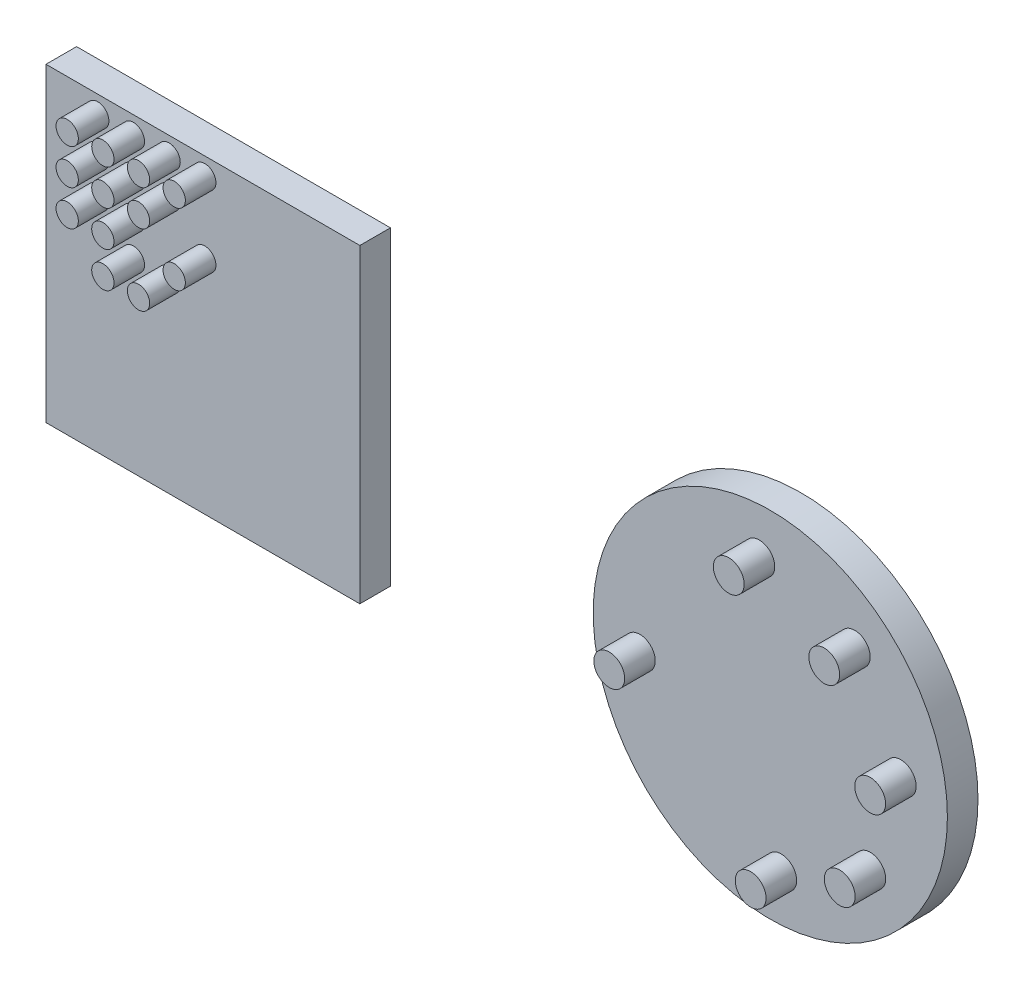
SolidWorks part; units mm, degrees
ref_plane "정면" through (0, 0, 0) normal (0, 0, 1) x (1, 0, 0)
ref_plane "윗면" through (0, 0, 0) normal (0, 1, 0) x (1, 0, 0)
ref_plane "우측면" through (0, 0, 0) normal (1, 0, 0) x (0, 0, -1)
sketch "스케치1" plane through (0, 0, 0) normal (0, 0, 1) x (1, 0, 0)
  circle A0 centre (-7.0097, -12.8826) radius 21.8715
extrude "보스-돌출1" add sketch "스케치1" along normal blind 60
sketch "스케치2" plane through (0, 0, 0) normal (0, 0, -1) x (-1, 0, 0)
  line L1 (-507.2126, 21.9087) -> (108.5736, 21.9087)
  line L2 (-507.2126, 21.9087) -> (-507.2126, -587.0489)
  line L3 (-507.2126, -587.0489) -> (108.5736, -587.0489)
  line L4 (108.5736, 21.9087) -> (108.5736, -587.0489)
  point P4 (-303.0554, 21.9087)
  point P5 (-507.2126, -587.0489)
extrude "보스-돌출2" add sketch "스케치2" along normal blind 60
pattern_linear "선형 패턴1" count 4 spacing 70 along (1, 0, 0) count 4 spacing 70 along (0, -1, 0) skipping (0, 3), (2, 2), (3, 1), (3, 3) of "보스-돌출1"
sketch "스케치3" plane through (0, 0, 0) normal (0, 0, 1) x (1, 0, 0)
  circle A0 centre (1372.5403, -312.891) radius 347.5261
extrude "보스-돌출3" add sketch "스케치3" along normal blind 60 separate body
sketch "스케치4" plane through (0, 0, 60) normal (0, 0, 1) x (1, 0, 0)
  circle A0 centre (1538.3435, -116.6992) radius 30.2418
extrude "보스-돌출4" add sketch "스케치4" along normal blind 60
pattern_circular "원형 패턴1" count 8 over 360 about axis through (1372.5403, -312.891, 0) along (0, 0, 1) skipping 2, 4 of "보스-돌출4"
